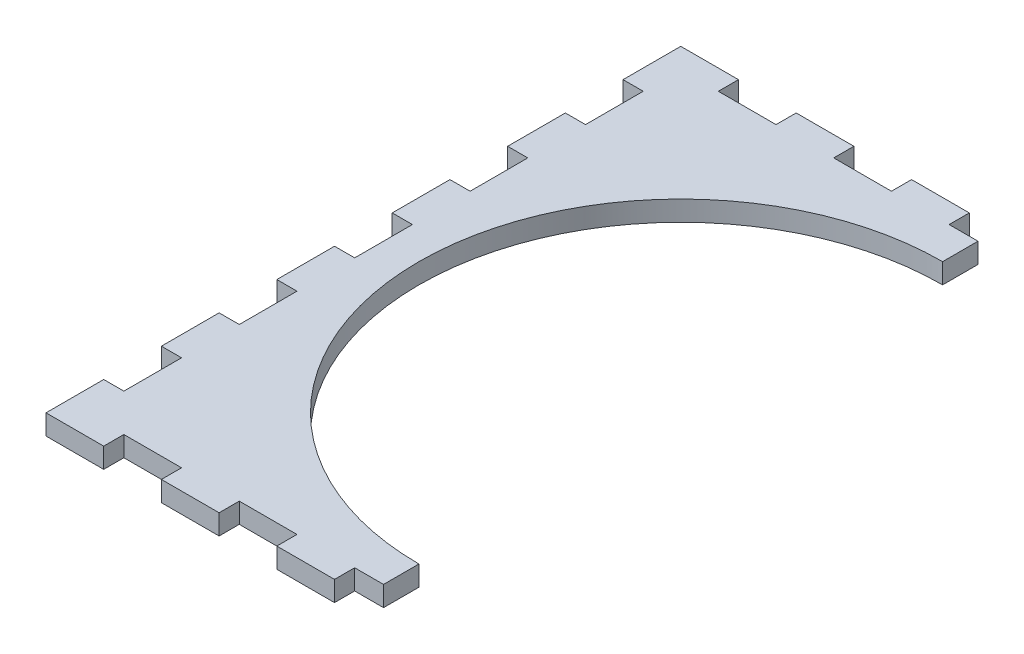
SolidWorks part; units mm, degrees
material "Pin"
ref_plane "Plan de face" through (0, 0, 0) normal (0, 0, 1) x (1, 0, 0)
ref_plane "Plan de dessus" through (0, 0, 0) normal (0, 1, 0) x (1, 0, 0)
ref_plane "Plan de droite" through (0, 0, 0) normal (1, 0, 0) x (0, 0, -1)
sketch "Esquisse1" plane through (0, 0, 0) normal (0, 1, 0) x (1, 0, 0)
  line L0 (0, -82.5) -> (0, -100)
  line L1 (0, 100) -> (-100, 100)
  line L2 (0, 100) -> (0, 82.5)
  line L3 (0, -100) -> (-100, -100)
  line L4 (-100, 100) -> (-100, -100)
  arc A0 (0, 82.5) -> (0, -82.5) centre (0, 0) ccw
  point P6 (-100, 0)
  dimension "D3" = 165
  dimension "D1" = 200
  dimension "D2" = 100
extrude "Boss.-Extru.1" add sketch "Esquisse1" along normal blind 6.35
sketch "Esquisse2" plane through (0, 6.35, 0) normal (0, 1, 0) x (1, 0, 0)
  line L0 (-100, -100) -> (0, -100) construction
  line L1 (-81.82, -100) -> (-63.64, -100)
  line L2 (-81.82, -100) -> (-81.82, -93.65)
  line L3 (-81.82, -93.65) -> (-63.64, -93.65)
  line L4 (-63.64, -100) -> (-63.64, -93.65)
  line L5 (-100, -100) -> (-81.82, -100) construction
  line L6 (-45.46, -100) -> (-27.28, -100)
  line L7 (-45.46, -100) -> (-45.46, -93.65)
  line L8 (-45.46, -93.65) -> (-27.28, -93.65)
  line L9 (-27.28, -100) -> (-27.28, -93.65)
  line L10 (-9.1, -100) -> (9.08, -100)
  line L11 (-9.1, -100) -> (-9.1, -93.65)
  line L12 (-9.1, -93.65) -> (9.08, -93.65)
  line L13 (9.08, -100) -> (9.08, -93.65)
  line L14 (-63.64, -100) -> (-45.46, -100) construction
  line L15 (-27.28, -100) -> (-9.1, -100) construction
  line L16 (-100, 100) -> (-100, -100) construction
  line L17 (-100, -81.8182) -> (-93.65, -81.8182)
  line L18 (-100, -81.8182) -> (-100, -63.6364)
  line L19 (-100, -63.6364) -> (-93.65, -63.6364)
  line L20 (-93.65, -81.8182) -> (-93.65, -63.6364)
  line L21 (0, 100) -> (-100, 100) construction
  line L22 (-100, -45.4545) -> (-93.65, -45.4545)
  line L23 (-100, -45.4545) -> (-100, -27.2727)
  line L24 (-100, -27.2727) -> (-93.65, -27.2727)
  line L25 (-93.65, -45.4545) -> (-93.65, -27.2727)
  line L26 (-100, -9.0909) -> (-93.65, -9.0909)
  line L27 (-100, -9.0909) -> (-100, 9.0909)
  line L28 (-100, 9.0909) -> (-93.65, 9.0909)
  line L29 (-93.65, -9.0909) -> (-93.65, 9.0909)
  line L30 (-100, 27.2727) -> (-93.65, 27.2727)
  line L31 (-100, 27.2727) -> (-100, 45.4545)
  line L32 (-100, 45.4545) -> (-93.65, 45.4545)
  line L33 (-93.65, 27.2727) -> (-93.65, 45.4545)
  line L34 (-100, 63.6364) -> (-93.65, 63.6364)
  line L35 (-100, 63.6364) -> (-100, 81.8182)
  line L36 (-100, 81.8182) -> (-93.65, 81.8182)
  line L37 (-93.65, 63.6364) -> (-93.65, 81.8182)
  line L42 (-81.8182, 100) -> (-63.6364, 100)
  line L43 (-81.8182, 100) -> (-81.8182, 93.65)
  line L44 (-81.8182, 93.65) -> (-63.6364, 93.65)
  line L45 (-63.6364, 100) -> (-63.6364, 93.65)
  line L46 (-100, 100) -> (-81.8182, 100) construction
  line L47 (-45.4545, 100) -> (-27.2727, 100)
  line L48 (-45.4545, 100) -> (-45.4545, 93.65)
  line L49 (-45.4545, 93.65) -> (-27.2727, 93.65)
  line L50 (-27.2727, 100) -> (-27.2727, 93.65)
  line L51 (-9.0909, 100) -> (9.0891, 100)
  line L52 (-9.0909, 100) -> (-9.0909, 93.65)
  line L53 (-9.0909, 93.65) -> (9.0891, 93.65)
  line L54 (9.0891, 100) -> (9.0891, 93.65)
  line L55 (-63.6364, 100) -> (-45.4545, 100) construction
  line L56 (-27.2727, 100) -> (-9.0909, 100) construction
  line L57 (-100, 81.8182) -> (-100, 100) construction
  line L58 (-100, 63.6364) -> (-100, 45.4545) construction
  line L59 (-100, 27.2727) -> (-100, 9.0909) construction
  line L60 (-100, -9.0909) -> (-100, -27.2727) construction
  line L61 (-100, -45.4545) -> (-100, -63.6364) construction
  line L62 (-100, -81.8182) -> (-100, -100) construction
  dimension "D1" = 18.18
  dimension "D2" = 6.35
  dimension "D3" = 6.35
  dimension "D4" = 6.35
  dimension "D5" = 18.18
extrude "Enlèv. mat.-Extru.1" cut sketch "Esquisse2" against normal blind 6.35
